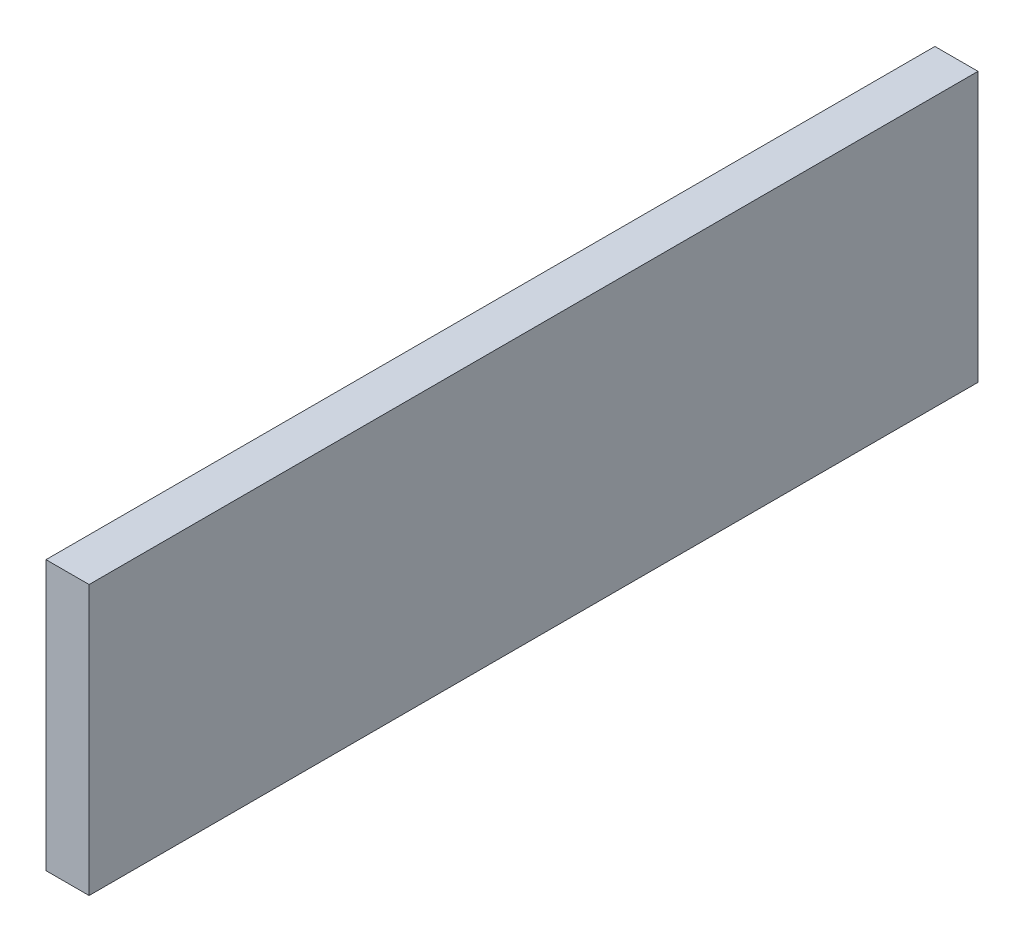
SolidWorks part; units mm, degrees
material "Perspex (TM) GS Acrylic Cast Sheet"
ref_plane "Front Plane" through (0, 0, 0) normal (0, 0, 1) x (1, 0, 0)
ref_plane "Top Plane" through (0, 0, 0) normal (0, 1, 0) x (1, 0, 0)
ref_plane "Right Plane" through (0, 0, 0) normal (1, 0, 0) x (0, 0, -1)
sketch "Sketch1" plane through (0, 0, 0) normal (1, 0, 0) x (0, 0, -1)
  line L0 (-70, 12.5) -> (-70, -12.5)
  line L2 (12.5, 12.5) -> (12.5, -12.5)
  line L19 (-70, 12.5) -> (12.5, 12.5)
  line L20 (-70, -12.5) -> (12.5, -12.5)
  circle A0 centre (0, 0) radius 4 construction
  point P3 (12.5, 0)
  point P18 (0, 0)
  dimension "D1" = 8
  dimension "D2" = 25
  dimension "D5" = 70
  dimension "D6" = 12.5
extrude "Boss-Extrude1" add sketch "Sketch1" along normal blind 4
sketch "Sketch2" plane through (4, 0, 0) normal (1, 0, 0) x (0, 0, -1)
  line L0 (0, 0) -> (-70, 0) construction
  line L1 (-70, 12.5) -> (-70, -12.5) construction
  point P0 (0, 0)
